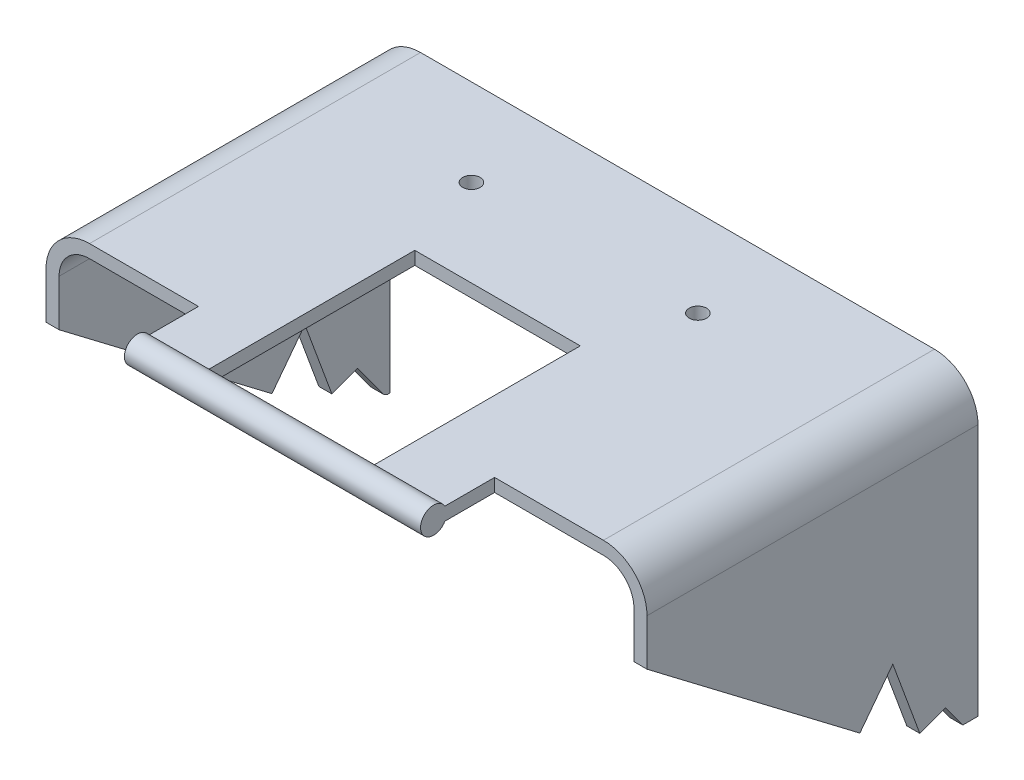
SolidWorks part; units mm, degrees
ref_plane "Front Plane" through (0, 0, 0) normal (0, 0, 1) x (1, 0, 0)
ref_plane "Top Plane" through (0, 0, 0) normal (0, 1, 0) x (1, 0, 0)
ref_plane "Right Plane" through (0, 0, 0) normal (1, 0, 0) x (0, 0, -1)
sketch "Sketch1" plane through (0, 0, 0) normal (0, 0, 1) x (1, 0, 0)
  line L0 (-57.6814, 0) -> (60.3186, 0)
  line L1 (70.3186, -10) -> (70.3186, -68)
  line L3 (-67.6814, -71.2087) -> (-67.6814, -10)
  arc A0 (60.3186, 0) -> (70.3186, -10) centre (60.3186, -10) cw
  arc A1 (-57.6814, 0) -> (-67.6814, -10) centre (-57.6814, -10) ccw
  point P7 (70.3186, 0)
  point P10 (-67.6814, 0)
  dimension "D2" = 10
  dimension "D1" = 138
  dimension "D3" = 68
extrude "Extrude-Thin1" add sketch "Sketch1" along normal blind 90 thin
sketch "Sketch2" plane through (-67.6814, 0, 0) normal (-1, 0, 0) x (0, 0, 1)
  line L0 (0, -71.4694) -> (90, -26.0774) construction
  line L1 (90, -71.2087) -> (90, -10) construction
  line L2 (90, -71.2087) -> (90, -10)
  line L3 (90, -71.2087) -> (0, -71.2087) construction
  line L4 (90, -10) -> (27.1196, -57.7915)
  line L5 (27.1196, -57.7915) -> (19.5641, -47.8505)
  line L6 (19.5641, -47.8505) -> (13.3487, -64.7369)
  line L7 (13.3487, -64.7369) -> (7.4357, -62.5605)
  line L8 (7.4357, -62.5605) -> (1.525, -70.7003)
  line L9 (1.525, -70.7003) -> (0, -71.4694)
  line L10 (0, -71.4694) -> (90, -71.2087)
extrude "Cut-Extrude1" cut sketch "Sketch2" against normal through all
sketch "Sketch3" plane through (0, 0, 0) normal (0, 1, 0) x (1, 0, 0)
  line L0 (26, -20) -> (-26, -20) construction
  line L1 (-57.6814, 0) -> (60.3186, 0) construction
  line L2 (70.3186, -90) -> (70.3186, 0) construction
  line L3 (35.3186, -76) -> (70.3186, -76)
  line L4 (35.3186, -76) -> (35.3186, -90)
  line L5 (35.3186, -90) -> (70.3186, -90)
  line L6 (70.3186, -76) -> (70.3186, -90)
  line L7 (-32.6814, -76) -> (-67.6814, -76)
  line L8 (-32.6814, -76) -> (-32.6814, -90)
  line L9 (-32.6814, -90) -> (-67.6814, -90)
  line L10 (-67.6814, -76) -> (-67.6814, -90)
  line L11 (19, -40) -> (-19, -40)
  line L12 (19, -40) -> (19, -90)
  line L13 (19, -90) -> (-19, -90)
  line L14 (-19, -40) -> (-19, -90)
  line L15 (-67.6814, -90) -> (-67.6814, 0) construction
  line L16 (-57.6814, -90) -> (60.3186, -90) construction
  circle A0 centre (26, -20) radius 2
  circle A1 centre (-26, -20) radius 2
  point P4 (0, -20)
  point P31 (0, -40)
  dimension "D1" = 4
  dimension "D2" = 20
  dimension "D3" = 52
  dimension "D4" = 35
  dimension "D5" = 38
  dimension "D6" = 50
  dimension "D7" = 14
extrude "Cut-Extrude2" cut sketch "Sketch3" against normal through all
sketch "Sketch4" plane through (-32.6814, 0, 0) normal (-1, 0, 0) x (0, 0, 1)
  line L0 (90, -3) -> (90, 0) construction
  circle A0 centre (90, -1.5) radius 3
  dimension "D1" = 6
extrude "Boss-Extrude1" add sketch "Sketch4" against normal up to surface (68 mm away) up to face at (35.3186, -1.5, 83)
